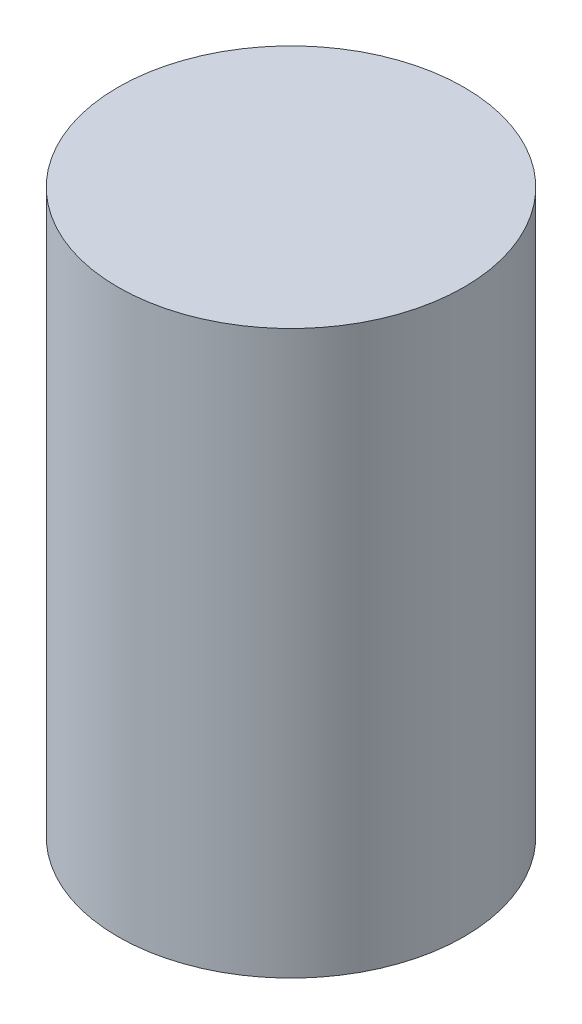
SolidWorks part; units mm, degrees
ref_plane "Front Plane" through (0, 0, 0) normal (0, 0, 1) x (1, 0, 0)
ref_plane "Top Plane" through (0, 0, 0) normal (0, 1, 0) x (1, 0, 0)
ref_plane "Right Plane" through (0, 0, 0) normal (1, 0, 0) x (0, 0, -1)
sketch "Sketch1" plane through (0, 0, 0) normal (0, 1, 0) x (1, 0, 0)
  circle A0 centre (-44, 44) radius 8
extrude "Can" add sketch "Sketch1" along normal blind 26 from offset 3
